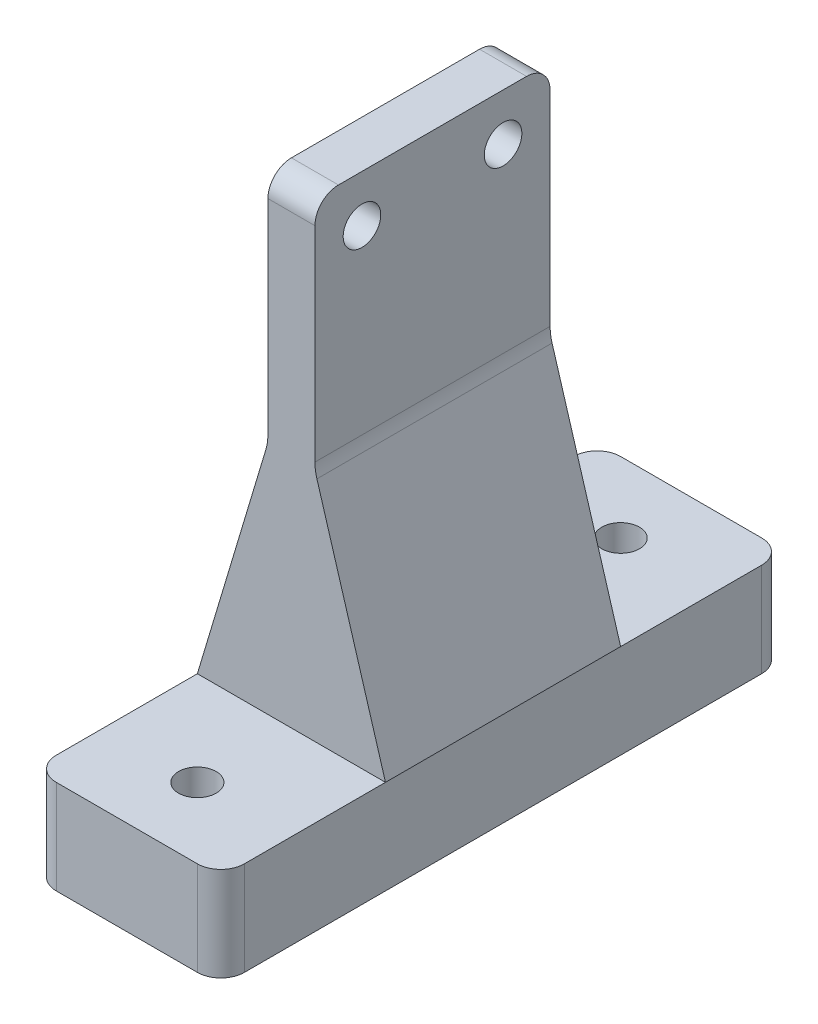
SolidWorks part; units mm, degrees
ref_plane "Front Plane" through (0, 0, 0) normal (0, 0, 1) x (1, 0, 0)
ref_plane "Top Plane" through (0, 0, 0) normal (0, 1, 0) x (1, 0, 0)
ref_plane "Right Plane" through (0, 0, 0) normal (1, 0, 0) x (0, 0, -1)
sketch "Sketch1" plane through (0, 0, 0) normal (0, 1, 0) x (1, 0, 0)
  line L0 (-25, 30) -> (-25, -30)
  line L5 (15, 30) -> (15, -30)
  line L9 (-25, 70) -> (15, 70)
  line L10 (15, 30) -> (15, 70)
  line L11 (-25, 70) -> (-25, 30)
  line L14 (-25, -50) -> (15, -50)
  line L15 (15, -30) -> (15, -50)
  line L16 (-25, -50) -> (-25, -30)
  line L19 (-25, 30) -> (-25, 45)
  point P0 (0, 0)
  dimension "D4" = 40
  dimension "D5" = 20
  dimension "D6" = 40
  dimension "D7" = 40
extrude "Boss-Extrude1" add sketch "Sketch1" along normal blind 20
sketch "Sketch2" plane through (0, 20, 0) normal (0, 1, 0) x (1, 0, 0)
  line L0 (-25, -50) -> (15, -50) construction
  line L1 (15, -50) -> (15, 70) construction
  line L8 (-10, 35) -> (0, 35)
  line L9 (0, 35) -> (0, -15)
  line L10 (-10, -15) -> (0, -15)
  line L11 (-10, 35) -> (-10, -15)
  dimension "D1" = 10
  dimension "D2" = 50
  dimension "D4" = 15
  dimension "D3" = 35
extrude "Boss-Extrude2" add sketch "Sketch2" along normal blind 100
sketch "Sketch4" plane through (0, 20, 0) normal (0, 1, 0) x (1, 0, 0)
  line L0 (-5, 70) -> (-5, -50) construction
  line L1 (-25, 70) -> (15, 70) construction
  line L2 (-25, -50) -> (15, -50) construction
  circle A0 centre (-5, 55) radius 4
  circle A1 centre (-5, -35) radius 4
  dimension "D2" = 8
  dimension "D3" = 8
  dimension "D1" = 15
  dimension "D4" = 15
extrude "Cut-Extrude2" cut sketch "Sketch4" against normal through all
fillet "Fillet1" radius 5 6 edges at (15, 10, -70) (15, 10, 50) (-25, 10, 50) (-25, 10, -70) (-5, 120, 15) (-5, 120, -35)
sketch "Sketch7" plane through (-10, 0, 0) normal (-1, 0, 0) x (0, 0, 1)
  line L0 (15, 115) -> (15, 20) construction
  line L1 (-35, 115) -> (-35, 20) construction
  line L2 (-30, 120) -> (10, 120) construction
  circle A0 centre (-25, 110) radius 4
  circle A1 centre (5, 110) radius 4
  dimension "D1" = 8
  dimension "D4" = 8
  dimension "D2" = 10
  dimension "D3" = 10
  dimension "D5" = 10
  dimension "D6" = 10
extrude "Cut-Extrude3" cut sketch "Sketch7" against normal through all
ref_plane "Plane2" through (0, 0, 15) normal (0, 0, 1) x (1, 0, 0)
sketch "Sketch9" plane through (0, 0, 15) normal (0, 0, 1) x (1, 0, 0)
  line L0 (-10, 20) -> (-25, 20)
  line L1 (-10, 20) -> (-10, 70)
  line L2 (-10, 115) -> (-10, 20) construction
  line L3 (-10, 70) -> (-25, 20)
  dimension "D1" = 15
  dimension "D2" = 50
extrude "Boss-Extrude3" add sketch "Sketch9" against normal blind 50
fillet "Fillet2" radius 10 1 edges at (-10, 70, -10)
sketch "Sketch10" plane through (0, 0, 15) normal (0, 0, 1) x (1, 0, 0)
  line L0 (0, 20) -> (15, 20)
  line L1 (0, 20) -> (0, 70)
  line L2 (0, 115) -> (0, 20) construction
  line L4 (0, 70) -> (15, 20)
  dimension "D1" = 15
  dimension "D2" = 50
extrude "Boss-Extrude4" add sketch "Sketch10" against normal blind 50
fillet "Fillet3" radius 10 1 edges at (0, 70, -10)
